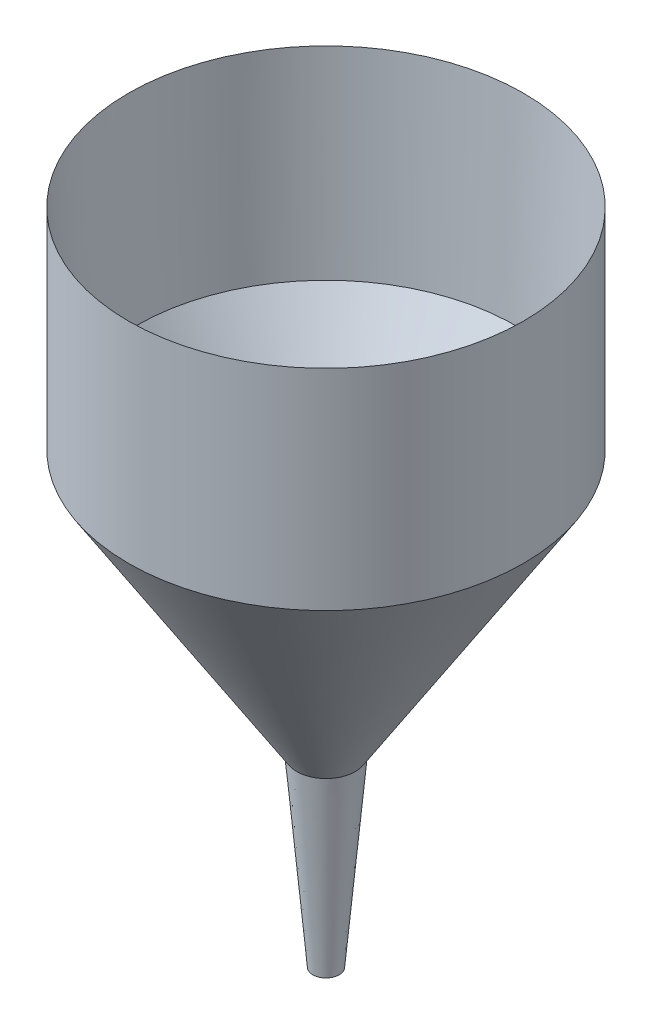
SolidWorks part; units mm, degrees
ref_plane "Front Plane" through (0, 0, 0) normal (0, 0, 1) x (1, 0, 0)
ref_plane "Top Plane" through (0, 0, 0) normal (0, 1, 0) x (1, 0, 0)
ref_plane "Right Plane" through (0, 0, 0) normal (1, 0, 0) x (0, 0, -1)
sketch "Sketch2" plane through (0, 0, 0) normal (0, 0, 1) x (1, 0, 0)
  line L0 (0, 50) -> (0, -36.2857) construction
  line L1 (-15, 50) -> (-15, 34.0636)
  line L2 (-15, 34.0636) -> (-2.2232, 13.9816)
  line L3 (-2.2232, 13.9816) -> (-1, 0)
  line L4 (-1, 0) -> (-1, 13.9219)
  line L5 (-1, 13.9219) -> (-14.4107, 35.0002)
  line L6 (-14.4107, 35.0002) -> (-15, 50)
  line L7 (19.0302, 0) -> (-21.0302, 0) construction
  dimension "D1" = 50
  dimension "D2" = 2
  dimension "D3" = 5
  dimension "D4" = 1
  dimension "D5" = 2.25
  dimension "D6" = 20.082
  dimension "D7" = 15.9364
  dimension "D8" = 15
revolve "Revolve3" add sketch "Sketch2" angle 360 about L0
